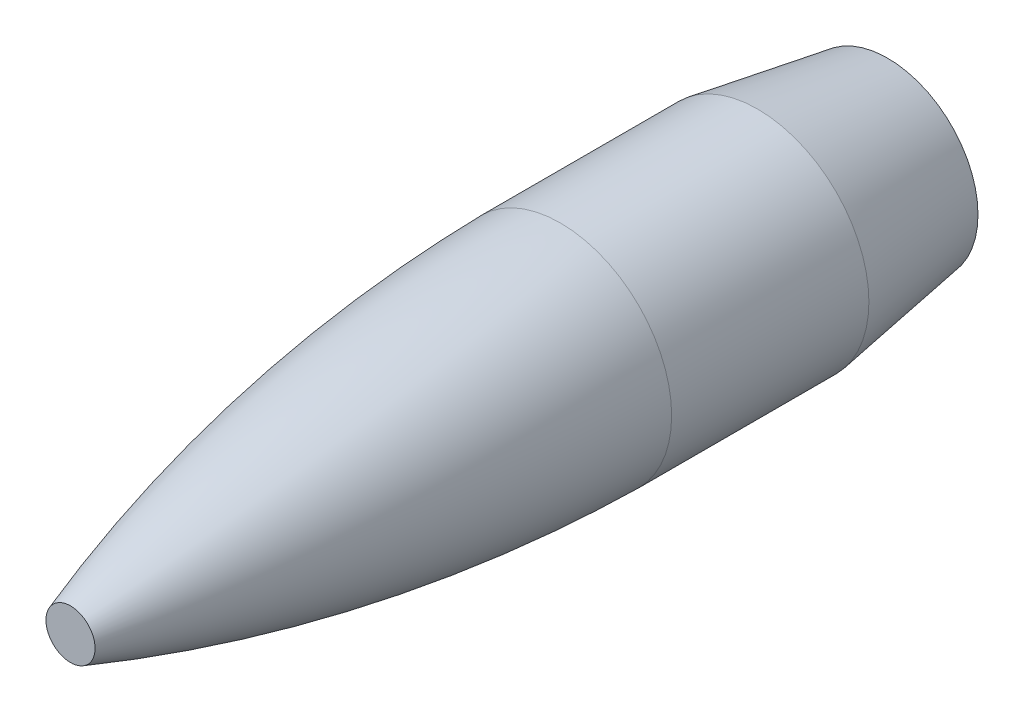
SolidWorks part; units mm, degrees
ref_plane "Front Plane" through (0, 0, 0) normal (0, 0, 1) x (1, 0, 0)
ref_plane "Top Plane" through (0, 0, 0) normal (0, 1, 0) x (1, 0, 0)
ref_plane "Right Plane" through (0, 0, 0) normal (1, 0, 0) x (0, 0, -1)
sketch ".308 Winchester" plane through (0, 0, 0) normal (0, 1, 0) x (1, 0, 0)
  line L1 (3.9116, -28.7274) -> (0, -28.7274) construction
  line L2 (3.9116, -28.7274) -> (3.9116, -11.5062) construction
  line L6 (3.9116, -4.572) -> (3.175, 0)
  line L7 (3.175, 0) -> (0, 0)
  line L8 (0, -28.7274) -> (0, 0)
  line L9 (0, -28.7274) -> (0.8636, -28.7274)
  line L10 (3.9116, -4.572) -> (3.9116, -11.5062)
  arc A0 (0.8636, -28.7274) -> (3.9116, -11.5062) centre (-50.8448, -10.6951) ccw
  dimension "D6" = 54.7624
  dimension "D9" = 50.8448
  dimension "D10" = 10.6951
  dimension "D4" = 3.175
  dimension "D5" = 3.9116
  dimension "D2" = 4.572
  dimension "D3" = 0.8636
  dimension "D7" = 6.9342
  dimension "D8" = 17.2212
  dimension "D11" = 28.7274
revolve "Revolve2" add sketch ".308 Winchester" angle 360 about L8
sketch "Sketch2" [suppressed] plane through (0, 0, 0) normal (0, 1, 0) x (1, 0, 0)
  line L0 (-3.9116, -11.5062) -> (-3.9116, -4.572)
  line L1 (-3.9116, -4.572) -> (-3.175, 0)
  line L2 (10.2616, 6.35) -> (-10.2616, 6.35)
  line L3 (-10.2616, -35.0774) -> (-10.2616, 6.35)
  line L4 (-10.2616, -35.0774) -> (10.2616, -35.0774)
  line L5 (3.9116, -4.572) -> (3.175, 0)
  line L6 (3.175, 0) -> (0, 0)
  line L7 (0, 0) -> (0, -28.7274)
  line L8 (0, -28.7274) -> (0.8636, -28.7274)
  line L9 (3.9116, -11.5062) -> (3.9116, -4.572)
  line L10 (3.9116, -4.572) -> (3.175, 0)
  line L11 (3.175, 0) -> (-3.175, 0)
  line L12 (0, 0) -> (0, -28.7274) construction
  line L13 (-0.8636, -28.7274) -> (0.8636, -28.7274)
  line L14 (3.9116, -11.5062) -> (3.9116, -4.572)
  line L15 (10.2616, -35.0774) -> (10.2616, 6.35)
  line L16 (3.175, 6.35) -> (-3.175, 6.35) construction
  line L17 (-10.2616, -11.5062) -> (-10.2616, -4.572) construction
  line L18 (-0.8636, -35.0774) -> (0.8636, -35.0774) construction
  arc A0 (-0.8636, -28.7274) -> (-3.9116, -11.5062) centre (50.8448, -10.6951) cw
  arc A1 (0.8636, -28.7274) -> (3.9116, -11.5062) centre (-50.8448, -10.6951) ccw
  arc A2 (0.8636, -28.7274) -> (3.9116, -11.5062) centre (-50.8448, -10.6951) ccw
  dimension "D5" = 6.35
  dimension "D1" = 0
  dimension "D2" = 6.35
  dimension "D3" = 6.35
  dimension "D4" = 6.35
extrude "Boss-Extrude1" [suppressed] add sketch "Sketch2" along normal blind 2
ref_plane "Plane2" [suppressed] through (0, 0.3, 0) normal (0, -1, 0) x (-1, 0, 0)
split line "Split Line3" [suppressed]
chamfer "Chamfer2" [suppressed] distance 0.7937 distance2 1.7
sketch ".308 Win. Text Bottom" [suppressed] plane through (0, 0, 0) normal (0, -1, 0) x (1, 0, 0)
  line L0 (-10.2616, 29.9974) -> (10.2616, 29.9974) construction
  line L1 (-10.2616, -6.35) -> (-10.2616, 35.0774) construction
  line L2 (10.2616, 35.0774) -> (10.2616, -6.35) construction
  line L3 (-10.2616, 35.0774) -> (10.2616, 35.0774) construction
  line L4 (-10.2616, -5.08) -> (10.2616, -5.08) construction
  line L5 (10.2616, -6.35) -> (-10.2616, -6.35) construction
  text T0 ".308 Win." font "Century Gothic" height 3.175
  text T1 "155gr Sierra" font "Dubai" height in points 8
  point P8 (0, 29.9974)
  dimension "D1" = 5.08
  dimension "D2" = 1.27
extrude "Bottom Text" [suppressed] cut sketch ".308 Win. Text Bottom" against normal blind 0.3
equation "\"d\"= .25'Boat tail diameter"
equation "\"_D\"= .154 * 2'Cylinder diameter"
equation "\"L_o\"= .678'Ogive length"
equation "\"L_c\"= .273'Cylinder length"
equation "\"L_F\"= .18'Frustum length"
equation "\"r\"= \"d\" / 2"
equation "\"_R\"= \"_D\" / 2"
equation "\"D_t\"= .068'Diameter of flattened tip"
equation "\"R_o\"= 2.156'Ogive radius"
equation "\"R_t\"= \"D_t\" / 2"
equation "\"theta_bt\"= 9deg'angle of boat tail from vertical"
equation "\"D6@.308 Winchester\" = \"R_o\""
equation "\"L_oal\"= 1.131'Overall length"
equation "\"D2@.308 Winchester\"=\"L_F\""
equation "\"D4@.308 Winchester\"=\"r\""
equation "\"D5@.308 Winchester\"=\"_R\""
equation "\"D3@.308 Winchester\"=\"R_t\""
equation "\"D7@.308 Winchester\"=\"L_c\""
equation "\"D8@.308 Winchester\"=\"L_o\""
